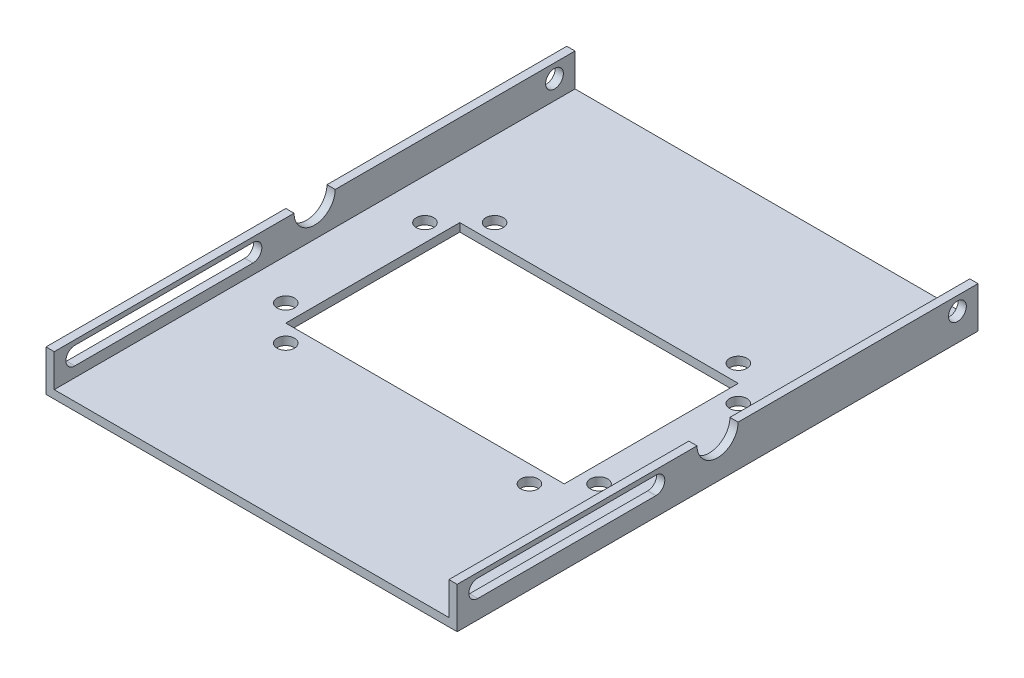
SolidWorks part; units mm, degrees
ref_plane "Front" through (0, 0, 0) normal (0, 0, 1) x (1, 0, 0)
ref_plane "Top" through (0, 0, 0) normal (0, 1, 0) x (1, 0, 0)
ref_plane "Right" through (0, 0, 0) normal (1, 0, 0) x (0, 0, -1)
sketch "Sketch1" plane through (0, 0, 0) normal (0, 0, 1) x (1, 0, 0)
  line L0 (-75, 0) -> (75, 0)
  line L1 (-75, 0) -> (-75, 15)
  line L2 (75, 0) -> (75, 15)
  point P4 (0, 0)
  dimension "D1" = 150
  dimension "D2" = 15
extrude "Extrude-Thin1" add sketch "Sketch1" along normal blind 95 and the other way blind 95 thin thin type one direction reverse wall 3
sketch "Sketch2" plane through (-75, 0, 0) normal (-1, 0, 0) x (0, 0, 1)
  line L0 (-95, 15) -> (95, 15) construction
  line L1 (-95, 15) -> (-95, 0) construction
  line L2 (87.5, 10) -> (22.5, 10) construction
  line L3 (87.5, 6.7615) -> (22.5, 6.7615)
  line L4 (87.5, 13.2385) -> (22.5, 13.2385)
  circle A0 centre (-87.5, 10) radius 3.2385
  arc A1 (87.5, 6.7615) -> (87.5, 13.2385) centre (87.5, 10) ccw
  arc A2 (22.5, 13.2385) -> (22.5, 6.7615) centre (22.5, 10) ccw
  point P8 (55, 10)
  dimension "D1" = 6.477
  dimension "D2" = 5
  dimension "D3" = 7.5
  dimension "D4" = 175
  dimension "D5" = 110
  dimension "D6" = 3.2385
extrude "Cut-Extrude1" cut sketch "Sketch2" against normal through all
sketch "Sketch3" plane through (75, 0, 0) normal (1, 0, 0) x (0, 0, -1)
  line L0 (95, 15) -> (-95, 15) construction
  circle A0 centre (0, 15) radius 7.5
  dimension "D1" = 15
extrude "Cut-Extrude2" cut sketch "Sketch3" against normal through all both and the other way through all
sketch "Sketch4" plane through (0, 3, 0) normal (0, 1, 0) x (1, 0, 0)
  line L0 (-50.8, 31.75) -> (50.8, 31.75)
  line L1 (-50.8, 31.75) -> (-50.8, -31.75)
  line L2 (-50.8, -31.75) -> (50.8, -31.75)
  line L3 (50.8, 31.75) -> (50.8, -31.75)
  line L4 (-50.8, 31.75) -> (50.8, -31.75) construction
  line L5 (-50.8, -31.75) -> (50.8, 31.75) construction
  circle A0 centre (-44.45, 38.1) radius 3.175
  circle A1 centre (44.45, 38.1) radius 3.175
  circle A2 centre (-44.45, -38.1) radius 3.175
  circle A3 centre (44.45, -38.1) radius 3.175
  circle A4 centre (-57.15, 25.4) radius 3.175
  circle A5 centre (57.15, 25.4) radius 3.175
  circle A6 centre (-57.15, -25.4) radius 3.175
  circle A7 centre (57.15, -25.4) radius 3.175
  point P0 (0, 0)
  dimension "D7" = 6.35
  dimension "D1" = 6.35
  dimension "D2" = 6.35
  dimension "D3" = 6.35
  dimension "D4" = 6.35
  dimension "D5" = 6.35
  dimension "D6" = 6.35
  dimension "D8" = 101.6
extrude "Cut-Extrude3" cut sketch "Sketch4" against normal blind 10
